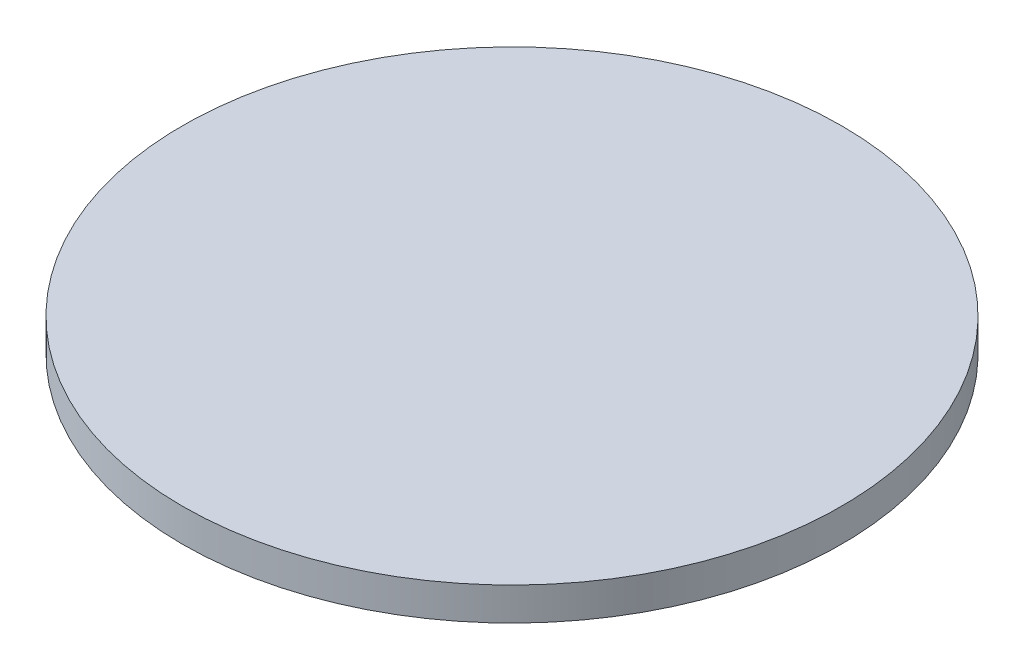
SolidWorks part; units mm, degrees
ref_plane "Front Plane" through (0, 0, 0) normal (0, 0, 1) x (1, 0, 0)
ref_plane "Top Plane" through (0, 0, 0) normal (0, 1, 0) x (1, 0, 0)
ref_plane "Right Plane" through (0, 0, 0) normal (1, 0, 0) x (0, 0, -1)
sketch "草图1" plane through (0, 0, 0) normal (0, 1, 0) x (1, 0, 0)
  circle A0 centre (0, 0) radius 20
  dimension "D1" = 40
extrude "凸台-拉伸1" add sketch "草图1" along normal mid plane 2
chamfer "倒角1" [suppressed] distance 0.2 angle 45
